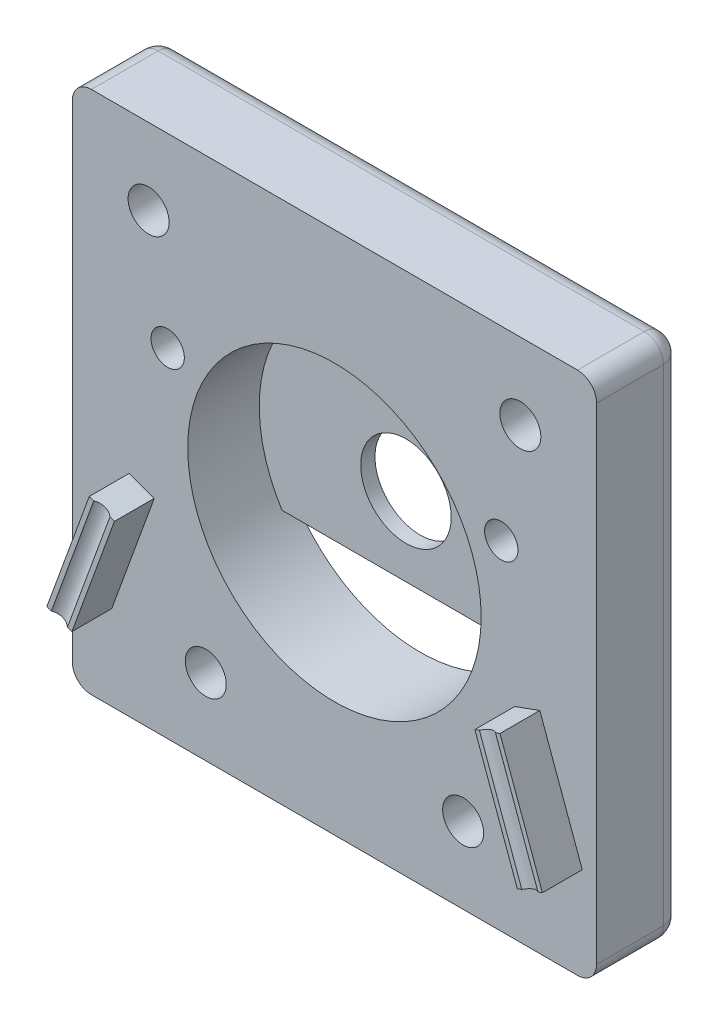
SolidWorks part; units mm, degrees
ref_plane "Front Plane" through (0, 0, 0) normal (0, 0, 1) x (1, 0, 0)
ref_plane "Top Plane" through (0, 0, 0) normal (0, 1, 0) x (1, 0, 0)
ref_plane "Right Plane" through (0, 0, 0) normal (1, 0, 0) x (0, 0, -1)
sketch "Sketch1" plane through (0, 0, 0) normal (0, 0, 1) x (1, 0, 0)
  line L1 (0, 0) -> (55, 0)
  line L2 (0, 0) -> (0, 55)
  line L3 (0, 55) -> (55, 55)
  line L4 (55, 0) -> (55, 55)
extrude "Boss-Extrude1" add sketch "Sketch1" along normal blind 9
ref_plane "Plane1" through (0, 0, 9) normal (0, 0, 1) x (1, 0, 0)
ref_plane "Plane2" through (0, 0, 0) normal (0, 0, -1) x (-1, 0, 0)
sketch "Sketch3" plane through (0, 0, 0) normal (0, 0, -1) x (-1, 0, 0)
  line L0 (-21.8123, 30.7838) -> (-14.8194, 34.8212) construction
  line L1 (-18.5, 32.6962) -> (-27.5, 27.5) construction
  circle A0 centre (-45, 35.5) radius 1.75
  circle A1 centre (-27.5, 27.5) radius 14.6423 construction
  circle A2 centre (-47, 47) radius 2.15
  circle A3 centre (-8, 47) radius 2.15
  circle A4 centre (-14, 8) radius 2.15
  circle A5 centre (-41, 8) radius 2.15
  circle A6 centre (-47, 47) radius 2.15 construction
  circle A7 centre (-8, 47) radius 2.15 construction
  circle A8 centre (-14, 8) radius 2.15 construction
  circle A9 centre (-41, 8) radius 2.15 construction
  circle A11 centre (-10, 35.5) radius 1.75
  circle A12 centre (-10, 35.5) radius 1.75 construction
  circle A13 centre (-45, 35.5) radius 1.75 construction
extrude "Cut-Extrude1" cut sketch "Sketch3" against normal through all
fillet "Fillet1" radius 2 8 edges at (27.5, 55, 0) (0, 27.5, 0) (27.5, 0, 0) (55, 55, 4.5) (55, 27.5, 0) (55, 0, 4.5) (0, 55, 4.5) (0, 0, 4.5)
sketch "Sketch9" plane through (0, 0, 0) normal (0, 1, 0) x (1, 0, 0)
  line L0 (0, 0) -> (0, -1.5) construction
  line L1 (0, -1.5) -> (0, -2) construction
  line L2 (0, -2) -> (0, -9) construction
  line L3 (0, -2) -> (0, -9) construction
  line L4 (55, -28.5) -> (55, -27) construction
  line L5 (55, -27) -> (55, -26.5) construction
  line L6 (55, -26.5) -> (55, -19.5) construction
sketch "Sketch4" plane through (0, 0, 0) normal (0, 0, -1) x (-1, 0, 0)
  circle A0 centre (-47, 47) radius 4.25
  circle A1 centre (-8, 47) radius 4.25
  circle A2 centre (-14, 8) radius 4.25
  circle A3 centre (-41, 8) radius 4.25
  dimension "D1" = 8.5
extrude "Cut-Extrude2" cut sketch "Sketch4" against normal blind 2.5
ref_plane "Plane3" through (3.0919, -8.495, 0) normal (-0.342, 0.9397, 0) x (0, 0, 1)
sketch "Sketch5" plane through (3.0919, -8.495, 0) normal (-0.342, 0.9397, 0) x (0, 0, 1)
  line L0 (13.1776, 53.6394) -> (9, 53.6394)
  line L2 (9, 53.6394) -> (9, 50.8394)
  line L3 (9, 50.8394) -> (13.1776, 50.8394)
  line L4 (9, 55.2394) -> (9, 46.2394) construction
  line L5 (14.25, 53.7394) -> (9, 53.7394) construction
  line L6 (13.1776, 53.6394) -> (13.1776, 53.1394)
  line L8 (13.1776, 51.3394) -> (13.1776, 50.8394)
  arc A0 (13.1776, 53.1394) -> (13.1776, 51.3394) centre (14.25, 52.2394) ccw
  dimension "D1" = 0.1
  dimension "D2" = 0.5
extrude "Boss-Extrude2" add sketch "Sketch5" along normal up to surface (13.0276 mm away)
ref_plane "Plane4" through (3.3418, 9.1816, 0) normal (-0.342, -0.9397, 0) x (0, 0, 1)
sketch "Sketch6" plane through (3.3418, 9.1816, 0) normal (-0.342, -0.9397, 0) x (0, 0, 1)
  line L0 (13.1776, 1.9563) -> (9, 1.9563)
  line L1 (9, -4.9437) -> (9, 3.0563) construction
  line L2 (9, 1.9563) -> (9, -0.8437)
  line L3 (9, -0.8437) -> (13.1776, -0.8437)
  line L4 (14.25, 2.0563) -> (9, 2.0563) construction
  line L5 (13.1776, 1.9563) -> (13.1776, 1.4563)
  line L7 (13.1776, -0.3437) -> (13.1776, -0.8437)
  arc A0 (13.1776, 1.4563) -> (13.1776, -0.3437) centre (14.25, 0.5563) ccw
  arc A1 (14.25, -0.9437) -> (14.25, 2.0563) centre (14.25, 0.5563) ccw construction
  dimension "D1" = 0.1
  dimension "D2" = 0.5
extrude "Boss-Extrude3" add sketch "Sketch6" against normal up to surface (13.0276 mm away)
sketch "Sketch7" plane through (0, 0, 9) normal (0, 0, 1) x (1, 0, 0)
  circle A0 centre (27.5, 27.5) radius 15.3923
  circle A1 centre (27.5, 27.5) radius 15.3923 construction
extrude "Cut-Extrude3" cut sketch "Sketch7" against normal up to vertex (7.5 mm away) up to point (0, 0, 1.5)
ref_plane "Plane5" through (0, 0, 1.5) normal (0, 0, 1) x (1, 0, 0)
sketch "Sketch8" plane through (0, 0, 1.5) normal (0, 0, 1) x (1, 0, 0)
  circle A0 centre (27.5, 27.5) radius 4.75
  circle A1 centre (27.5, 27.5) radius 4.75 construction
extrude "Cut-Extrude4" cut sketch "Sketch8" against normal through all
sketch "Sketch10" plane through (0, 0, 1.5) normal (0, 0, 1) x (1, 0, 0)
  line L0 (14.5, 19.2585) -> (40.5, 19.2585)
  arc A0 (14.5, 19.2585) -> (40.5, 19.2585) centre (27.5, 27.5) ccw
  circle A1 centre (27.5, 27.5) radius 15.3923 construction
  dimension "D1" = 26
extrude "Cut-Extrude5" cut sketch "Sketch10" against normal through all
